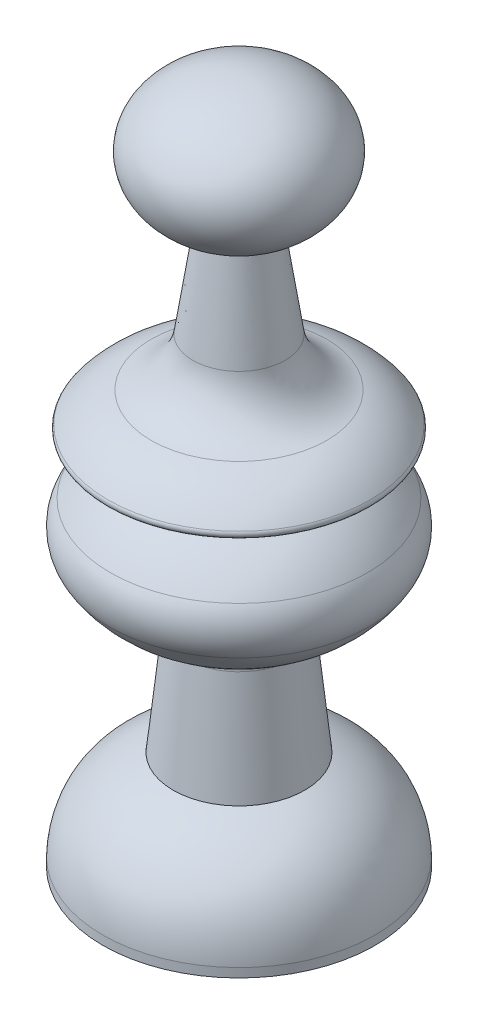
SolidWorks part; units mm, degrees
ref_plane "Front Plane" through (0, 0, 0) normal (0, 0, 1) x (1, 0, 0)
ref_plane "Top Plane" through (0, 0, 0) normal (0, 1, 0) x (1, 0, 0)
ref_plane "Right Plane" through (0, 0, 0) normal (1, 0, 0) x (0, 0, -1)
sketch "Sketch1" plane through (0, 0, 0) normal (0, 0, 1) x (1, 0, 0)
  line L0 (0, 0) -> (0, 57.15) construction
  line L1 (0, 0) -> (-11.5, 0)
  line L2 (-5.5562, 7.6173) -> (-4.6047, 16.755)
  line L3 (0, 30.1625) -> (-33.3364, 30.1625) construction
  line L4 (-11.5, 0) -> (-11.5, 57.15) construction
  line L5 (-4.4596, 30.086) -> (-4.4596, 30.988)
  line L6 (0, 57.15) -> (0, 0)
  line L7 (-4.4596, 30.988) -> (-11.5, 30.988)
  line L8 (0, 30.988) -> (-23.0188, 30.988) construction
  line L9 (-2.667, 46.3884) -> (-4.445, 34.5388)
  arc A0 (-10.8675, 26.1839) -> (-10.9384, 22.2413) centre (-7.944, 24.1594) ccw
  arc A3 (-4.6047, 16.755) -> (-5.7122, 18.3812) centre (-6.1205, 16.9129) ccw
  arc A4 (-10.9384, 22.2413) -> (-5.7122, 18.3812) centre (-3.2729, 27.1515) ccw
  arc A5 (-4.4596, 30.086) -> (-10.8675, 26.1839) centre (-3.2729, 20.9247) ccw
  ellipse E0 centre (0, 51.5874) end of major axis (7.5, 51.5874) minor radius 5.5626 (0, 57.15) -> (-2.667, 46.3884) ccw
  spline S0 degree 2 poles (-11.5, 0) (-11.2207, 5.5448) (-5.5562, 7.6173) knots 0 0 0 1 1 1
  spline S1 degree 2 poles (-11.5, 30.988) (-9.1982, 34.5483) (-4.445, 34.5388) knots 0 0 0 1 1 1
  point P16 (-4.7625, 15.24)
  dimension "D10" = 3.556
  dimension "D18" = 1.5768
  dimension "D1" = 57.15
  dimension "D2" = 23
  dimension "D3" = 9.525
  dimension "D4" = 11.1125
  dimension "D5" = 7.6173
  dimension "D6" = 3.5818
  dimension "D7" = 10.5804
  dimension "D8" = 15.24
  dimension "D9" = 30.1625
  dimension "D11" = 5.945
  dimension "D12" = 24.1594
  dimension "D13" = 20.9247
  dimension "D14" = 16.9129
  dimension "D15" = 6.1205
  dimension "D17" = 4.4596
  dimension "D19" = 1.3258
  dimension "D20" = 3.5508
  dimension "D16" = 30.988
  dimension "D21" = 4.445
  dimension "D22" = 15
  dimension "D23" = 11.1252
  dimension "D24" = 2.667
revolve "Revolve2" add sketch "Sketch1" angle 360 about L6
sketch "Sketch2" plane through (0, 0, 0) normal (0, -1, 0) x (1, 0, 0)
  circle A1 centre (0, 0) radius 11.5
  circle A2 centre (0, 0) radius 11.5
  dimension "D1" = 0
extrude "Boss-Extrude1" add sketch "Sketch2" along normal blind 0.762 separate body
fillet "Fillet3" radius 0.381 3 edges at (0, 30.988, 11.5) (0, 30.988, 4.4596) (0, 30.086, 4.4596)
fillet "Fillet4" radius 5.08 1 edges at (0, 34.5388, 4.445)
